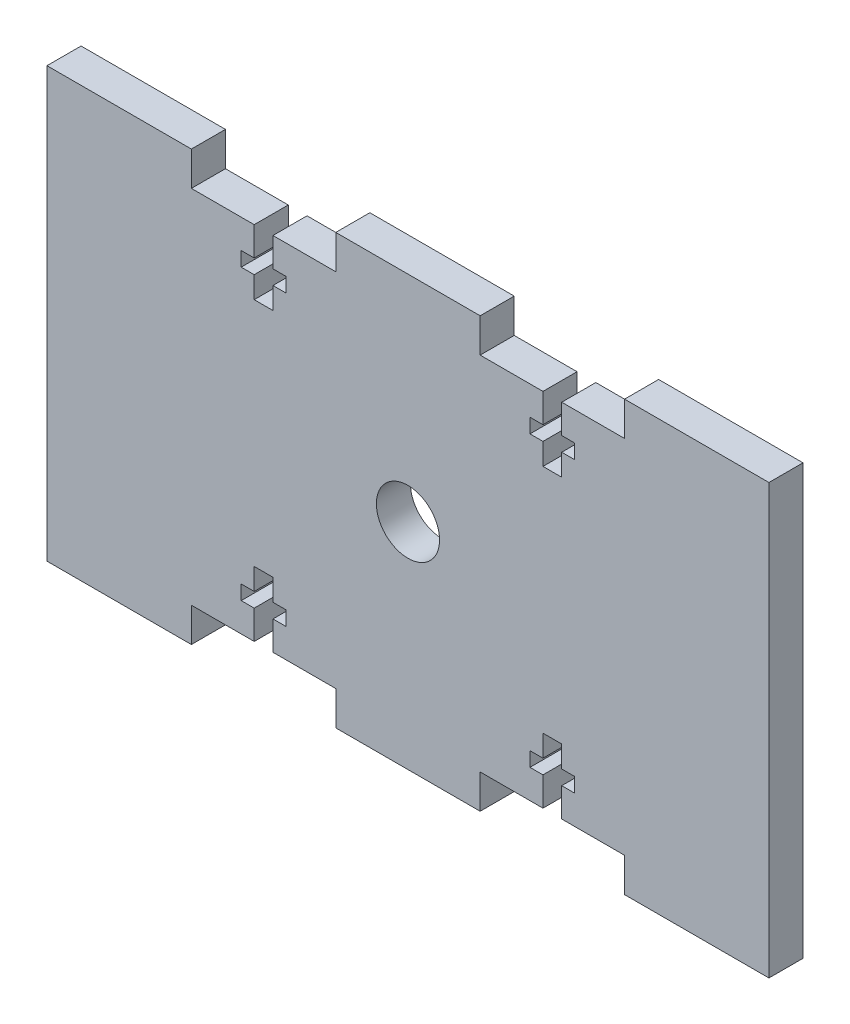
SolidWorks part; units mm, degrees
ref_plane "Front Plane" through (0, 0, 0) normal (0, 0, 1) x (1, 0, 0)
ref_plane "Top Plane" through (0, 0, 0) normal (0, 1, 0) x (1, 0, 0)
ref_plane "Right Plane" through (0, 0, 0) normal (1, 0, 0) x (0, 0, -1)
sketch "Sketch1" plane through (0, 0, 0) normal (0, 0, 1) x (1, 0, 0)
  line L0 (63.5, 75.4888) -> (63.5, 0) construction
  line L1 (25.4, 5.9944) -> (50.8, 5.9944)
  line L2 (0, 0) -> (0, 75.4888)
  line L3 (25.4, 69.4944) -> (50.8, 69.4944)
  line L4 (127, 0) -> (127, 75.4888)
  line L5 (76.2, 69.4944) -> (101.6, 69.4944)
  line L6 (127, 37.7444) -> (0, 37.7444) construction
  line L7 (0, 75.4888) -> (25.4, 75.4888)
  line L8 (25.4, 69.4944) -> (25.4, 75.4888)
  line L9 (101.6, 69.4944) -> (101.6, 75.4888)
  line L10 (50.8, 69.4944) -> (50.8, 75.4888)
  line L11 (50.8, 75.4888) -> (76.2, 75.4888)
  line L12 (76.2, 69.4944) -> (76.2, 75.4888)
  line L13 (127, 75.4888) -> (101.6, 75.4888)
  line L14 (127, 0) -> (101.6, 0)
  line L15 (76.2, 5.9944) -> (76.2, 0)
  line L16 (50.8, 0) -> (76.2, 0)
  line L17 (50.8, 5.9944) -> (50.8, 0)
  line L18 (101.6, 5.9944) -> (101.6, 0)
  line L19 (25.4, 5.9944) -> (25.4, 0)
  line L20 (0, 0) -> (25.4, 0)
  line L21 (76.2, 5.9944) -> (101.6, 5.9944)
  dimension "D1" = 25.4
  dimension "D2" = 25.4
  dimension "D3" = 127
  dimension "D4" = 5.9944
  dimension "D6" = 31.75
extrude "Boss-Extrude1" add sketch "Sketch1" along normal blind 5.9944
sketch "Sketch2" plane through (0, 0, 5.9944) normal (0, 0, 1) x (1, 0, 0)
  line L0 (63.5, 75.4888) -> (63.5, 0) construction
  line L1 (76.2, 75.4888) -> (50.8, 75.4888) construction
  line L2 (50.8, 0) -> (76.2, 0) construction
  line L3 (36.449, 69.4944) -> (36.449, 64.4144)
  line L4 (50.8, 69.4944) -> (25.4, 69.4944) construction
  line L5 (36.449, 64.4144) -> (34.163, 64.4144)
  line L6 (34.163, 64.4144) -> (34.163, 61.8744)
  line L7 (34.163, 61.8744) -> (36.449, 61.8744)
  line L8 (36.449, 61.8744) -> (36.449, 58.0644)
  line L9 (36.449, 58.0644) -> (39.751, 58.0644)
  line L10 (39.751, 58.0644) -> (39.751, 61.8744)
  line L11 (39.751, 61.8744) -> (42.037, 61.8744)
  line L12 (42.037, 61.8744) -> (42.037, 64.4144)
  line L13 (42.037, 64.4144) -> (39.751, 64.4144)
  line L14 (39.751, 64.4144) -> (39.751, 69.4944)
  line L15 (36.449, 69.4944) -> (39.751, 69.4944)
  line L16 (0, 37.7444) -> (127, 37.7444) construction
  line L17 (0, 75.4888) -> (0, 0) construction
  line L18 (127, 0) -> (127, 75.4888) construction
  line L19 (36.449, 5.9944) -> (39.751, 5.9944)
  line L20 (39.751, 11.0744) -> (39.751, 5.9944)
  line L21 (42.037, 11.0744) -> (39.751, 11.0744)
  line L22 (42.037, 13.6144) -> (42.037, 11.0744)
  line L23 (39.751, 13.6144) -> (42.037, 13.6144)
  line L24 (39.751, 17.4244) -> (39.751, 13.6144)
  line L25 (36.449, 17.4244) -> (39.751, 17.4244)
  line L26 (36.449, 13.6144) -> (36.449, 17.4244)
  line L27 (34.163, 13.6144) -> (36.449, 13.6144)
  line L28 (34.163, 11.0744) -> (34.163, 13.6144)
  line L29 (36.449, 11.0744) -> (34.163, 11.0744)
  line L30 (36.449, 5.9944) -> (36.449, 11.0744)
  line L31 (90.551, 5.9944) -> (90.551, 11.0744)
  line L32 (90.551, 11.0744) -> (92.837, 11.0744)
  line L33 (92.837, 11.0744) -> (92.837, 13.6144)
  line L34 (92.837, 13.6144) -> (90.551, 13.6144)
  line L35 (90.551, 13.6144) -> (90.551, 17.4244)
  line L36 (90.551, 17.4244) -> (87.249, 17.4244)
  line L37 (87.249, 17.4244) -> (87.249, 13.6144)
  line L38 (87.249, 13.6144) -> (84.963, 13.6144)
  line L39 (84.963, 13.6144) -> (84.963, 11.0744)
  line L40 (84.963, 11.0744) -> (87.249, 11.0744)
  line L41 (87.249, 11.0744) -> (87.249, 5.9944)
  line L42 (90.551, 5.9944) -> (87.249, 5.9944)
  line L43 (90.551, 69.4944) -> (87.249, 69.4944)
  line L44 (87.249, 64.4144) -> (87.249, 69.4944)
  line L45 (84.963, 64.4144) -> (87.249, 64.4144)
  line L46 (84.963, 61.8744) -> (84.963, 64.4144)
  line L47 (87.249, 61.8744) -> (84.963, 61.8744)
  line L48 (87.249, 58.0644) -> (87.249, 61.8744)
  line L49 (90.551, 58.0644) -> (87.249, 58.0644)
  line L50 (90.551, 61.8744) -> (90.551, 58.0644)
  line L51 (92.837, 61.8744) -> (90.551, 61.8744)
  line L52 (92.837, 64.4144) -> (92.837, 61.8744)
  line L53 (90.551, 64.4144) -> (92.837, 64.4144)
  line L54 (90.551, 69.4944) -> (90.551, 64.4144)
  point P10 (38.1, 69.4944)
  point P22 (38.1, 69.4944)
  point P40 (38.1, 5.9944)
  point P65 (88.9, 5.9944)
  point P66 (88.9, 69.4944)
  dimension "D1" = 3.302
  dimension "D2" = 11.43
  dimension "D3" = 2.286
  dimension "D4" = 2.54
  dimension "D5" = 5.08
extrude "Cut-Extrude2" cut sketch "Sketch2" against normal blind 5.9944
sketch "Sketch3" plane through (0, 0, 5.9944) normal (0, 0, 1) x (1, 0, 0)
  line L0 (63.5, 75.4888) -> (63.5, 0) construction
  line L1 (76.2, 75.4888) -> (50.8, 75.4888) construction
  line L2 (50.8, 0) -> (76.2, 0) construction
  line L3 (0, 37.7444) -> (127, 37.7444) construction
  line L4 (0, 75.4888) -> (0, 0) construction
  line L5 (127, 0) -> (127, 75.4888) construction
  circle A0 centre (63.5, 37.7444) radius 5.5563
  dimension "D1" = 11.1125
extrude "Cut-Extrude3" cut sketch "Sketch3" against normal blind 5.9944
